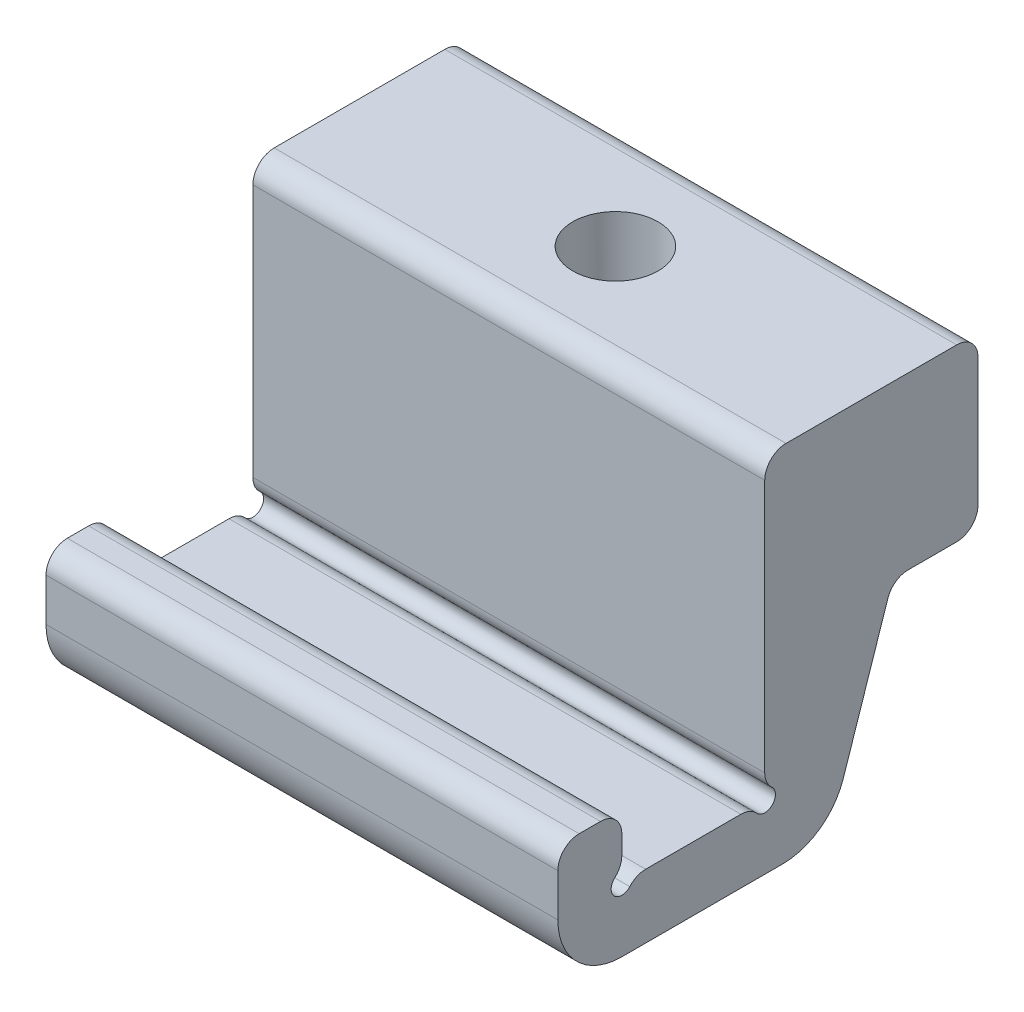
SolidWorks part; units mm, degrees
ref_plane "Front Plane" through (0, 0, 0) normal (0, 0, 1) x (1, 0, 0)
ref_plane "Top Plane" through (0, 0, 0) normal (0, 1, 0) x (1, 0, 0)
ref_plane "Right Plane" through (0, 0, 0) normal (1, 0, 0) x (0, 0, -1)
ref_plane "Plane2" through (-107.5, 40, 0) normal (1, 0, 0) x (0, 0, -1)
sketch "Sketch1" plane through (-107.5, 40, 0) normal (1, 0, 0) x (0, 0, -1)
  line L0 (-6.7, -37) -> (-6.7, -40)
  line L1 (-6.7, -40) -> (0, -40)
  line L2 (0, -40) -> (0, -26)
  line L3 (0, -26) -> (10, -26)
  line L5 (3, -43) -> (-9.7, -43)
  line L6 (-9.7, -43) -> (-9.7, -37)
  line L7 (-9.7, -37) -> (-6.7, -37)
  line L8 (-6.7, 0) -> (-6.7, -3) construction
  line L9 (0, -370) -> (0, -5) construction
  line L10 (3, -43) -> (6, -34)
  line L11 (-6.2, -40) -> (0, -40) construction
  line L12 (0, -25) -> (10, -25) construction
  line L13 (3, -43) -> (10, -34) construction
  line L15 (10, -34) -> (10, -26)
  line L16 (10, -34) -> (6, -34)
  dimension "D1" = 1
  dimension "D2" = 3
  dimension "D3" = 3
  dimension "D4" = 3
  dimension "D5" = 8
  dimension "D6" = 4
  dimension "D7" = 3
extrude "Boss-Extrude1" add sketch "Sketch1" along normal mid plane 24
fillet "Fillet1" radius 3 2 edges at (-107.5, -3, 9.7) (-107.5, -3, -3)
sketch "Sketch4" plane through (0, 0, 0) normal (1, 0, 0) x (0, 0, -1)
  circle A0 centre (-6.7, 0) radius 0.5
  circle A1 centre (0, 0) radius 0.5
  dimension "D1" = 1
extrude "Cut-Extrude3" cut sketch "Sketch4" against normal through all
fillet "Fillet2" radius 1 4 edges at (-107.5, 0, 6.2) (-107.5, 0, 0.5) (-107.5, 0.5, 0) (-107.5, 0.5, 6.7)
fillet "Fillet3" radius 1 2 edges at (-107.5, 3, 9.7) (-107.5, 3, 6.7)
fillet "Fillet4" radius 1 2 edges at (-107.5, 14, 0) (-107.5, 14, -10)
fillet "Fillet6" radius 1 2 edges at (-107.5, 6, -10) (-107.5, 6, -6)
sketch "Sketch2" plane through (0, 14, 0) normal (0, -1, 0) x (1, 0, 0)
  circle A2 centre (-107.5, -5) radius 2
  circle A3 centre (-107.5, -5) radius 2
  dimension "D1" = 0
extrude "Cut-Extrude1" cut sketch "Sketch2" along normal through all
sketch "Sketch6" plane through (0, 0, -10) normal (0, 0, -1) x (-1, 0, 0)
  line L0 (115.5, 14) -> (115.5, 10) construction
  line L1 (95.5, 14) -> (119.5, 14) construction
  line L2 (115.5, 10) -> (119.5, 10) construction
  line L3 (119.5, 7) -> (119.5, 13) construction
  line L4 (95.5, 10) -> (99.5, 10) construction
  line L5 (95.5, 7) -> (95.5, 13) construction
  circle A0 centre (115.5, 10) radius 2
  circle A1 centre (99.5, 10) radius 2
  dimension "D3" = 4
  dimension "D1" = 4
  dimension "D2" = 4
extrude "Cut-Extrude4" cut sketch "Sketch6" against normal blind 8
sketch "Sketch7" plane through (-107.5, 40, 0) normal (1, 0, 0) x (0, 0, -1)
  line L0 (5.1313, -25) -> (5.1313, -30.5) construction
  line L1 (1.8813, -30.5) -> (8.3813, -30.5)
  line L2 (1.8813, -30.5) -> (1.8813, -43)
  line L3 (1.8813, -43) -> (8.3813, -43)
  line L4 (8.3813, -30.5) -> (8.3813, -43) construction
  line L5 (5.1313, -43) -> (5.1313, -30.5) construction
  line L6 (1.8813, -36.75) -> (8.3813, -36.75) construction
  line L7 (1, -25) -> (9.2626, -25) construction
  line L10 (9, -26) -> (1, -26) construction
  line L11 (-6.7, -43) -> (0.8377, -43) construction
  line L14 (10, -30.5) -> (10, -43)
  line L15 (10, -43) -> (8.3813, -43)
  line L16 (10, -30.5) -> (8.3813, -30.5)
  line L17 (10, -33) -> (10, -27) construction
  point P192 (5.1313, -36.75)
  dimension "D1" = 6.5
  dimension "D2" = 4.5
extrude "Cut-Extrude5" cut sketch "Sketch7" against normal mid plane 6.5
